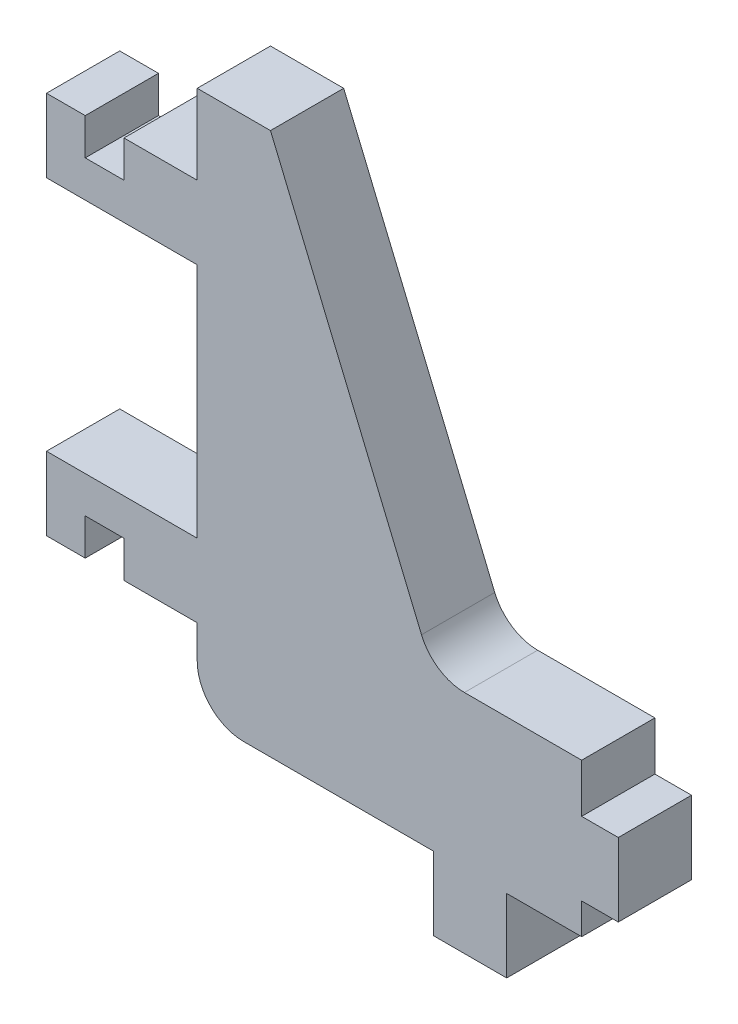
SolidWorks part; units mm, degrees
ref_plane "Front Plane" through (0, 0, 0) normal (0, 0, 1) x (1, 0, 0)
ref_plane "Top Plane" through (0, 0, 0) normal (0, 1, 0) x (1, 0, 0)
ref_plane "Right Plane" through (0, 0, 0) normal (1, 0, 0) x (0, 0, -1)
sketch "Sketch1" plane through (0, 0, 0) normal (0, 0, 1) x (1, 0, 0)
  line L0 (0, 0) -> (0, 44.45)
  line L1 (0, 22.225) -> (-18.5141, 22.225) construction
  line L2 (0, 6.525) -> (-6, 6.525)
  line L3 (-6, 6.525) -> (-6, 9.525)
  line L4 (-6, 9.525) -> (-9.175, 9.525)
  line L5 (-9.175, 9.525) -> (-9.175, 6.525)
  line L6 (-9.175, 6.525) -> (-12.35, 6.525)
  line L7 (-12.35, 6.525) -> (-12.35, 12.525)
  line L8 (-12.35, 12.525) -> (0, 12.525)
  line L9 (0, 37.925) -> (-6, 37.925)
  line L10 (-6, 37.925) -> (-6, 34.925)
  line L11 (-6, 34.925) -> (-9.175, 34.925)
  line L12 (-9.175, 34.925) -> (-9.175, 37.925)
  line L13 (-9.175, 37.925) -> (-12.35, 37.925)
  line L14 (-12.35, 37.925) -> (-12.35, 31.925)
  line L15 (-12.35, 31.925) -> (0, 31.925)
  line L16 (0, 0) -> (19.3548, 0)
  line L17 (19.3548, 0) -> (19.3548, -6)
  line L18 (19.3548, -6) -> (25.3548, -6)
  line L19 (25.3548, -6) -> (25.3548, 0)
  line L20 (25.3548, 0) -> (31.496, 0)
  line L21 (31.496, 0) -> (31.496, 2.54)
  line L22 (31.496, 2.54) -> (34.496, 2.54)
  line L23 (34.496, 2.54) -> (34.496, 8.54)
  line L24 (34.496, 8.54) -> (31.496, 8.54)
  line L25 (31.496, 8.54) -> (31.496, 12.525)
  line L26 (0, 44.45) -> (6, 44.45)
  line L27 (6, 44.45) -> (19.3548, 12.525)
  line L28 (19.3548, 12.525) -> (31.496, 12.525)
  point P13 (-12.35, 9.525)
  point P31 (32.996, 2.54)
  dimension "D1" = 44.45
  dimension "D2" = 6
  dimension "D3" = 6
  dimension "D4" = 3.175
  dimension "D5" = 3.175
  dimension "D6" = 3
  dimension "D7" = 12.7
  dimension "D8" = 19.3548
  dimension "D9" = 6
  dimension "D10" = 6
  dimension "D11" = 31.496
  dimension "D12" = 3
  dimension "D13" = 6
  dimension "D14" = 2.54
  dimension "D15" = 6
extrude "Boss-Extrude1" add sketch "Sketch1" along normal blind 6 contours L14 L15 L0 L9 L10 L11 L12 L13 | L28 L27 L26 L0 L16 L17 L18 L19 L20 L21 L22 L23 L24 L25 | L8 L7 L6 L5 L4 L3 L2 L0
fillet "Fillet1" radius 3.81 2 edges at (0, 0, 3) (19.3548, 12.525, 3)
